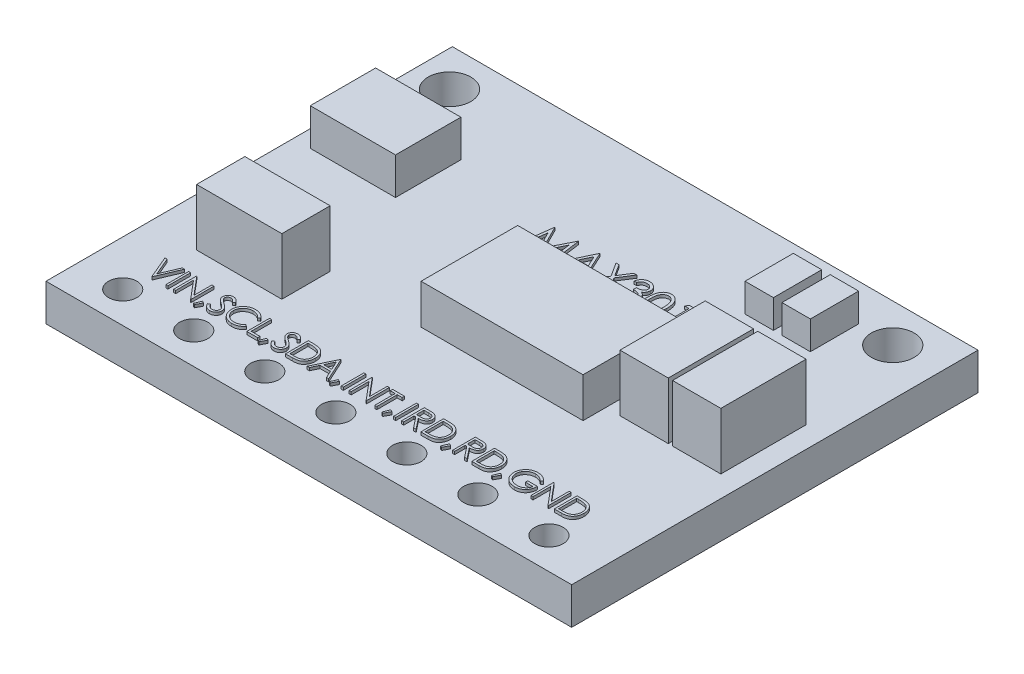
SolidWorks part; units mm, degrees
material "ABS"
ref_plane "前基準面" through (0, 0, 0) normal (0, 0, 1) x (1, 0, 0)
ref_plane "上基準面" through (0, 0, 0) normal (0, 1, 0) x (1, 0, 0)
ref_plane "右基準面" through (0, 0, 0) normal (1, 0, 0) x (0, 0, -1)
sketch "Sketch1" plane through (0, 0, 0) normal (0, 1, 0) x (1, 0, 0)
  line L1 (0, 0) -> (18.5, 0)
  line L2 (0, 0) -> (0, 14.3)
  line L3 (0, 14.3) -> (18.5, 14.3)
  line L4 (18.5, 0) -> (18.5, 14.3)
  dimension "D1" = 18.5
  dimension "D2" = 14.3
extrude "base" add sketch "Sketch1" along normal blind 1.3
sketch "Sketch2" plane through (0, 1.3, 0) normal (0, 1, 0) x (1, 0, 0)
  line L0 (1.1, 2.6925) -> (1.1, 0.6) construction
  line L1 (1.1, 0.6) -> (3.0984, 0.6) construction
  line L2 (0, 14.3) -> (0, 0) construction
  line L3 (0, 0) -> (18.5, 0) construction
  circle A0 centre (1.6, 1.1) radius 0.5
  dimension "D1" = 1
  dimension "D2" = 1.1
  dimension "D3" = 0.6
extrude "electrodes1" cut sketch "Sketch2" against normal through all
pattern_linear "electrodesN" count 7 spacing 2.5 along (1, 0, 0) of "electrodes1"
sketch "Sketch3" plane through (0, 1.3, 0) normal (0, 1, 0) x (1, 0, 0)
  line L0 (3.9938, 13.7) -> (0.5, 13.7) construction
  line L1 (0.5, 13.7) -> (0.5, 10.9717) construction
  line L2 (0, 14.3) -> (0, 0) construction
  line L3 (18.5, 14.3) -> (0, 14.3) construction
  circle A0 centre (1.25, 12.95) radius 0.75
  circle A1 centre (16.85, 12.95) radius 0.75
  dimension "D1" = 1.5
  dimension "D4" = 15.6
  dimension "D2" = 0.5
  dimension "D3" = 0.6
extrude "fixingHole" cut sketch "Sketch3" against normal through all
sketch "Sketch4" plane through (0, 1.3, 0) normal (0, 1, 0) x (1, 0, 0)
  line L0 (18.5, 0) -> (18.5, 14.3) construction
  line L1 (14.2, 9) -> (15.9, 9)
  line L2 (14.2, 9) -> (14.2, 6)
  line L3 (14.2, 6) -> (15.9, 6)
  line L4 (15.9, 9) -> (15.9, 6)
  line L5 (16.05, 9) -> (17.75, 9)
  line L6 (16.05, 9) -> (16.05, 6)
  line L7 (16.05, 6) -> (17.75, 6)
  line L8 (17.75, 9) -> (17.75, 6)
  line L9 (1.7, 3.6) -> (4.7, 3.6)
  line L10 (1.7, 3.6) -> (1.7, 5.3)
  line L11 (1.7, 5.3) -> (4.7, 5.3)
  line L12 (4.7, 3.6) -> (4.7, 5.3)
  line L13 (0, 0) -> (18.5, 0) construction
  line L14 (0, 14.3) -> (0, 0) construction
  dimension "D1" = 3
  dimension "D2" = 1.7
  dimension "D3" = 4.3
  dimension "D4" = 3.55
  dimension "D5" = 9
  dimension "D6" = 4.7
  dimension "D7" = 5.3
extrude "component1" add sketch "Sketch4" along normal blind 2
sketch "Sketch5" plane through (0, 1.3, 0) normal (0, 1, 0) x (1, 0, 0)
  line L0 (0, 0) -> (18.5, 0) construction
  line L1 (8, 8.6) -> (13.7, 8.6)
  line L2 (8, 8.6) -> (8, 5.2)
  line L3 (8, 5.2) -> (13.7, 5.2)
  line L4 (13.7, 8.6) -> (13.7, 5.2)
  line L5 (18.5, 0) -> (18.5, 14.3) construction
  dimension "D1" = 5.7
  dimension "D2" = 3.4
  dimension "D3" = 8.6
  dimension "D4" = 10.5
extrude "sensor" add sketch "Sketch5" along normal blind 1.4
sketch "Sketch6" plane through (0, 1.3, 0) normal (0, 1, 0) x (1, 0, 0)
  line L0 (18.5, 0) -> (18.5, 14.3) construction
  line L1 (14.6, 13) -> (15.6, 13)
  line L2 (14.6, 13) -> (14.6, 11.3)
  line L3 (14.6, 11.3) -> (15.6, 11.3)
  line L4 (15.6, 13) -> (15.6, 11.3)
  line L5 (14.3, 13) -> (13.3, 13)
  line L6 (14.3, 13) -> (14.3, 11.3)
  line L7 (14.3, 11.3) -> (13.3, 11.3)
  line L8 (13.3, 13) -> (13.3, 11.3)
  line L9 (18.5, 14.3) -> (0, 14.3) construction
  dimension "D1" = 1
  dimension "D2" = 1.7
  dimension "D3" = 5.2
  dimension "D4" = 3
  dimension "D5" = 2.3
extrude "component2" add sketch "Sketch6" along normal blind 1
sketch "Sketch7" plane through (0, 1.3, 0) normal (0, 1, 0) x (1, 0, 0)
  line L0 (0, 14.3) -> (0, 0) construction
  line L1 (0.6, 11) -> (3.6, 11)
  line L2 (0.6, 11) -> (0.6, 8.7)
  line L3 (0.6, 8.7) -> (3.6, 8.7)
  line L4 (3.6, 11) -> (3.6, 8.7)
  line L5 (0, 0) -> (18.5, 0) construction
  dimension "D1" = 3
  dimension "D2" = 2.3
  dimension "D3" = 3.6
  dimension "D4" = 11
extrude "component3" add sketch "Sketch7" along normal blind 1.3
sketch "Sketch8" plane through (0, 1.3, 0) normal (0, 1, 0) x (1, 0, 0)
  text T0 "MAX30102" font "Century Gothic" height 1
  text T1 "VIN,SCL,SDA,INT,IRD,RD,GND" font "Century Gothic" height 0.8
extrude "text" add sketch "Sketch8" along normal blind 0.1
